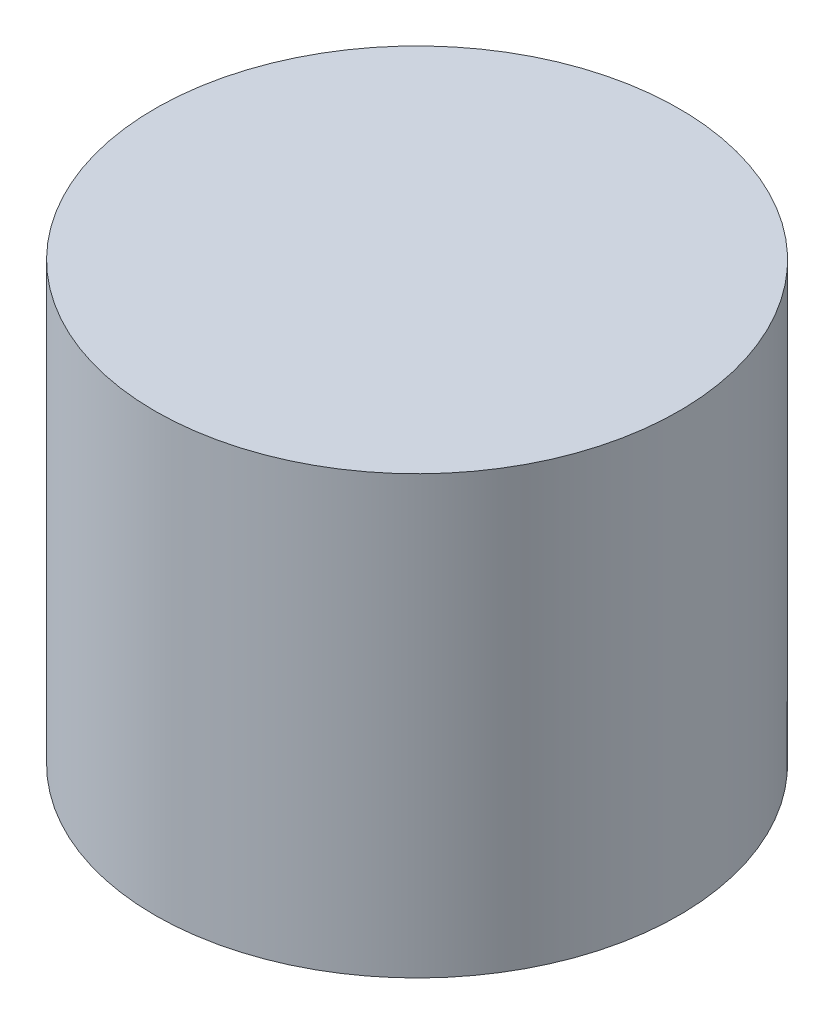
SolidWorks part; units mm, degrees
ref_plane "Front Plane" through (0, 0, 0) normal (0, 0, 1) x (1, 0, 0)
ref_plane "Top Plane" through (0, 0, 0) normal (0, 1, 0) x (1, 0, 0)
ref_plane "Right Plane" through (0, 0, 0) normal (1, 0, 0) x (0, 0, -1)
sketch "Sketch1" plane through (0, 0, 0) normal (0, 1, 0) x (1, 0, 0)
  circle A0 centre (0, 0) radius 90
  dimension "D1" = 180
extrude "Boss-Extrude1" add sketch "Sketch1" along normal blind 150
shell "Shell1" thickness 12
